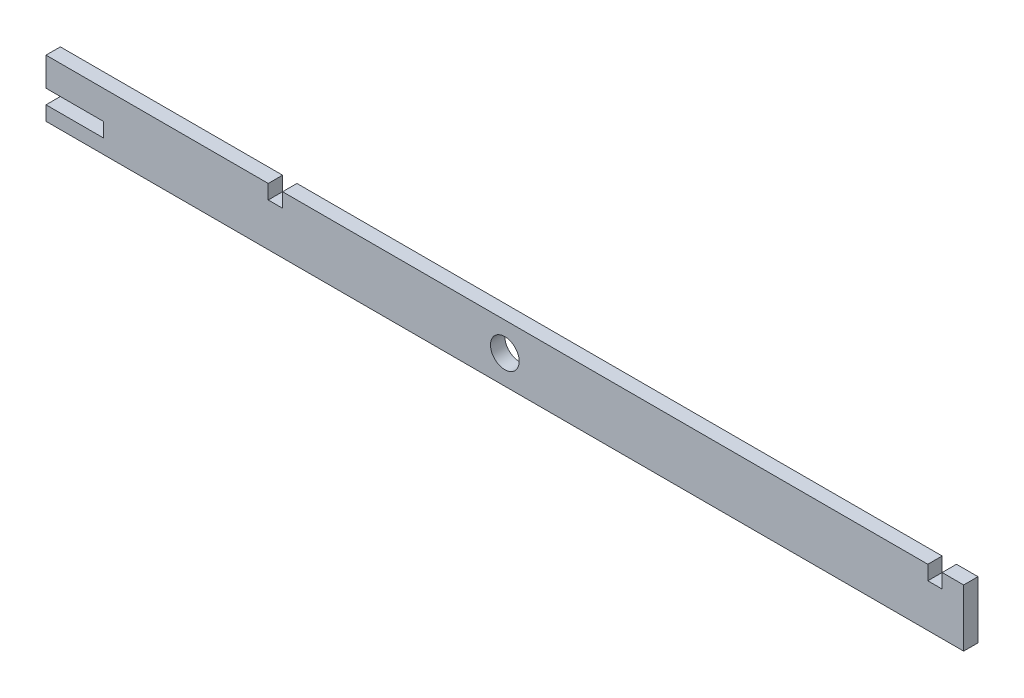
SolidWorks part; units mm, degrees
ref_plane "Front Plane" through (0, 0, 0) normal (0, 0, 1) x (1, 0, 0)
ref_plane "Top Plane" through (0, 0, 0) normal (0, 1, 0) x (1, 0, 0)
ref_plane "Right Plane" through (0, 0, 0) normal (1, 0, 0) x (0, 0, -1)
sketch "Sketch2" plane through (0, 0, 0) normal (0, 0, 1) x (1, 0, 0)
  line L0 (0, 0) -> (-203.2, 0)
  line L1 (-203.2, 0) -> (-203.2, -12.7)
  line L2 (-203.2, -12.7) -> (0, -12.7)
  line L3 (0, -12.7) -> (0, 0)
  line L4 (0, -6.35) -> (-6.35, -6.35) construction
  line L5 (-6.35, -6.35) -> (-6.35, -3.175) construction
  line L6 (-7.9375, -3.175) -> (-4.7625, -3.175)
  line L7 (-7.9375, -3.175) -> (-7.9375, 0)
  line L8 (-4.7625, -3.175) -> (-4.7625, 0)
  line L9 (-101.6, 0) -> (-101.6, -6.35) construction
  line L10 (0, -6.35) -> (-101.6, -6.35) construction
  line L11 (-203.2, -6.35) -> (-190.5, -6.35)
  line L12 (-190.5, -6.35) -> (-190.5, -9.525)
  line L13 (-190.5, -9.525) -> (-203.2, -9.525)
  line L14 (-101.6, -6.35) -> (-152.4, -6.35) construction
  line L15 (-152.4, -6.35) -> (-152.4, -3.175) construction
  line L16 (-153.9875, -3.175) -> (-150.8125, -3.175)
  line L17 (-150.8125, -3.175) -> (-150.8125, 0)
  line L18 (-153.9875, -3.175) -> (-153.9875, 0)
  circle A0 centre (-101.6, -6.35) radius 3.175
  point P11 (-6.35, -3.175)
  point P25 (-152.4, -3.175)
  dimension "D6" = 6.35
  dimension "D1" = 203.2
  dimension "D2" = 12.7
  dimension "D3" = 6.35
  dimension "D4" = 3.175
  dimension "D5" = 3.175
  dimension "D7" = 12.7
  dimension "D8" = 3.175
  dimension "D9" = 50.8
  dimension "D10" = 3.175
  dimension "D11" = 3.175
extrude "Boss-Extrude1" add sketch "Sketch2" along normal blind 3.175 contours L12 L13 L1 L2 L3 L0 L8 L6 L7 L11 A0
